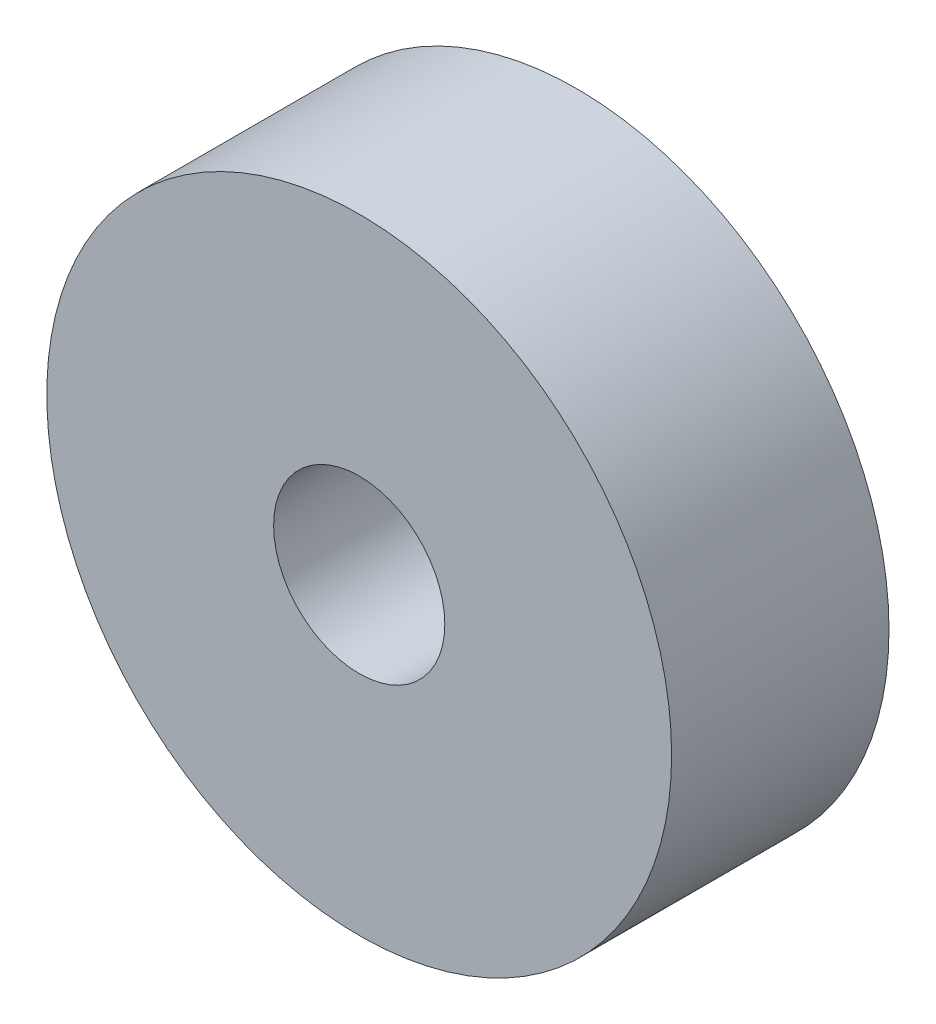
SolidWorks part; units mm, degrees
ref_plane "前视基准面" through (0, 0, 0) normal (0, 0, 1) x (1, 0, 0)
ref_plane "上视基准面" through (0, 0, 0) normal (0, 1, 0) x (1, 0, 0)
ref_plane "右视基准面" through (0, 0, 0) normal (1, 0, 0) x (0, 0, -1)
sketch "草图1" plane through (0, 0, 0) normal (0, 0, 1) x (1, 0, 0)
  circle A0 centre (0, 0) radius 3.65
  circle A1 centre (0, 0) radius 1
  dimension "D1" = 2
  dimension "D2" = 7.3
extrude "凸台-拉伸1" add sketch "草图1" along normal blind 2.54
sketch "草图2" plane through (0, 0, 0) normal (0, 0, -1) x (-1, 0, 0)
  circle A0 centre (0, 0) radius 1.45
  dimension "D1" = 2.9
extrude "切除-拉伸1" cut sketch "草图2" against normal blind 0.85
